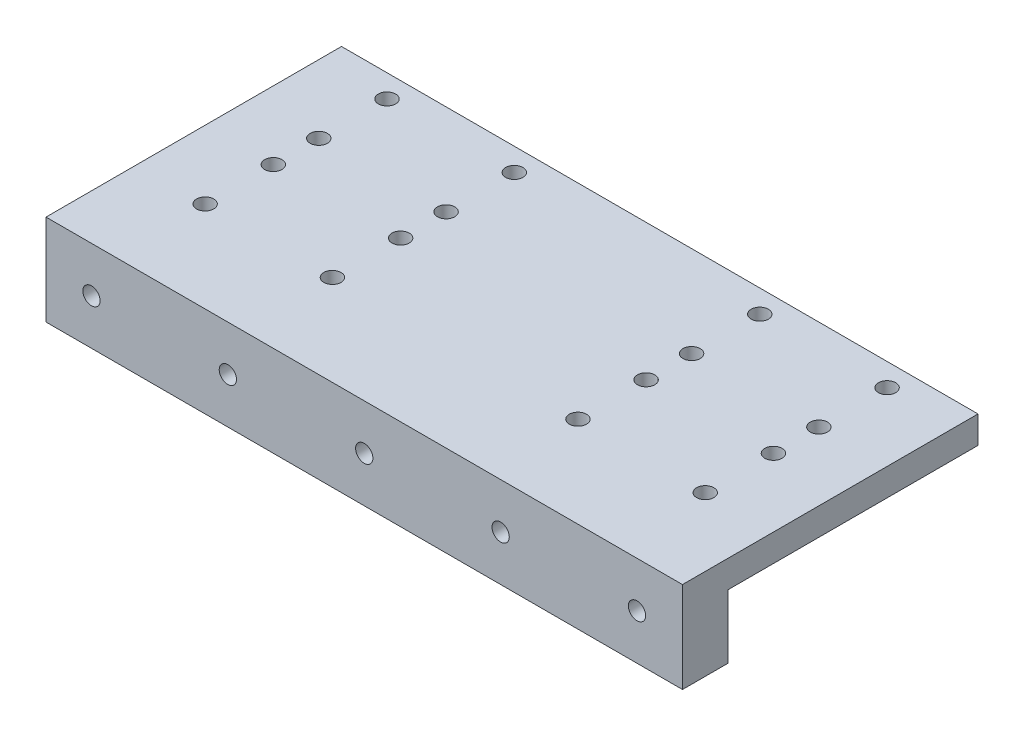
SolidWorks part; units mm, degrees
ref_plane "前视基准面" through (0, 0, 0) normal (0, 0, 1) x (1, 0, 0)
ref_plane "上视基准面" through (0, 0, 0) normal (0, 1, 0) x (1, 0, 0)
ref_plane "右视基准面" through (0, 0, 0) normal (1, 0, 0) x (0, 0, -1)
other "Configuration Table"
sketch "草图1" plane through (0, 0, 0) normal (0, 0, 1) x (1, 0, 0)
  line L0 (10, -10) -> (40, -10) construction
  line L1 (0, 0) -> (140, 0)
  line L2 (0, 0) -> (0, -20)
  line L3 (0, -20) -> (140, -20)
  line L4 (140, 0) -> (140, -20)
  circle A0 centre (10, -10) radius 1.9
  circle A1 centre (40, -10) radius 1.9
  circle A2 centre (70, -10) radius 1.9
  circle A3 centre (100, -10) radius 1.9
  circle A4 centre (130, -10) radius 1.9
  dimension "D2" = 3.8
  dimension "D7" = 10
  dimension "D1" = 140
  dimension "D4" = 30
  dimension "D5" = 10
  dimension "D6" = 20
  dimension "D3" = 5
extrude "凸台-拉伸1" add sketch "草图1" along normal blind 10
sketch "草图2" plane through (0, 0, 0) normal (-1, 0, 0) x (0, 0, 1)
  line L1 (10, 0) -> (-55, 0)
  line L2 (10, 0) -> (10, -6)
  line L3 (10, -6) -> (-55, -6)
  line L4 (-55, 0) -> (-55, -6)
  dimension "D1" = 65
  dimension "D2" = 6
extrude "凸台-拉伸2" add sketch "草图2" against normal through all
sketch "草图3" plane through (0, -6, 0) normal (0, -1, 0) x (1, 0, 0)
  line L0 (140, -55) -> (0, -55) construction
  line L1 (15, -35) -> (43, -35)
  line L2 (15, -35) -> (15, -50)
  line L3 (15, -50) -> (43, -50)
  line L4 (43, -35) -> (43, -50)
  line L5 (0, -55) -> (0, 0) construction
  line L6 (15, -35) -> (15, -10) construction
  line L7 (43, -50) -> (125, -50) construction
  circle A0 centre (15, -35) radius 1.9
  circle A1 centre (43, -35) radius 1.9
  circle A2 centre (15, -50) radius 1.9
  circle A3 centre (43, -50) radius 1.9
  circle A4 centre (15, -10) radius 1.9
  circle A5 centre (15, -25) radius 1.9
  circle A6 centre (43, -10) radius 1.9
  circle A7 centre (43, -25) radius 1.9
  circle A8 centre (125, -50) radius 1.9
  circle A9 centre (125, -35) radius 1.9
  circle A10 centre (125, -25) radius 1.9
  circle A11 centre (125, -10) radius 1.9
  circle A12 centre (97, -10) radius 1.9
  circle A13 centre (97, -25) radius 1.9
  circle A14 centre (97, -35) radius 1.9
  circle A15 centre (97, -50) radius 1.9
  dimension "D5" = 3.8
  dimension "D6" = 3.8
  dimension "D7" = 3.8
  dimension "D8" = 3.8
  dimension "D1" = 15
  dimension "D2" = 28
  dimension "D3" = 5
  dimension "D4" = 15
  dimension "D10" = 25
  dimension "D12" = 82
  dimension "D9" = 2
  dimension "D11" = 2
extrude "切除-拉伸1" cut sketch "草图3" against normal blind 10 contours L4 A1 L1 | L1 A1 L4 | L3 A3 L4 | L3 A2 L2 | L2 A2 L3 | L1 A0 L2 | L2 A0 L1 | A4 | A5 | A7 | A6 | A12 | A14 | A15 | A8 | A9 | A10 | A11 | A13
